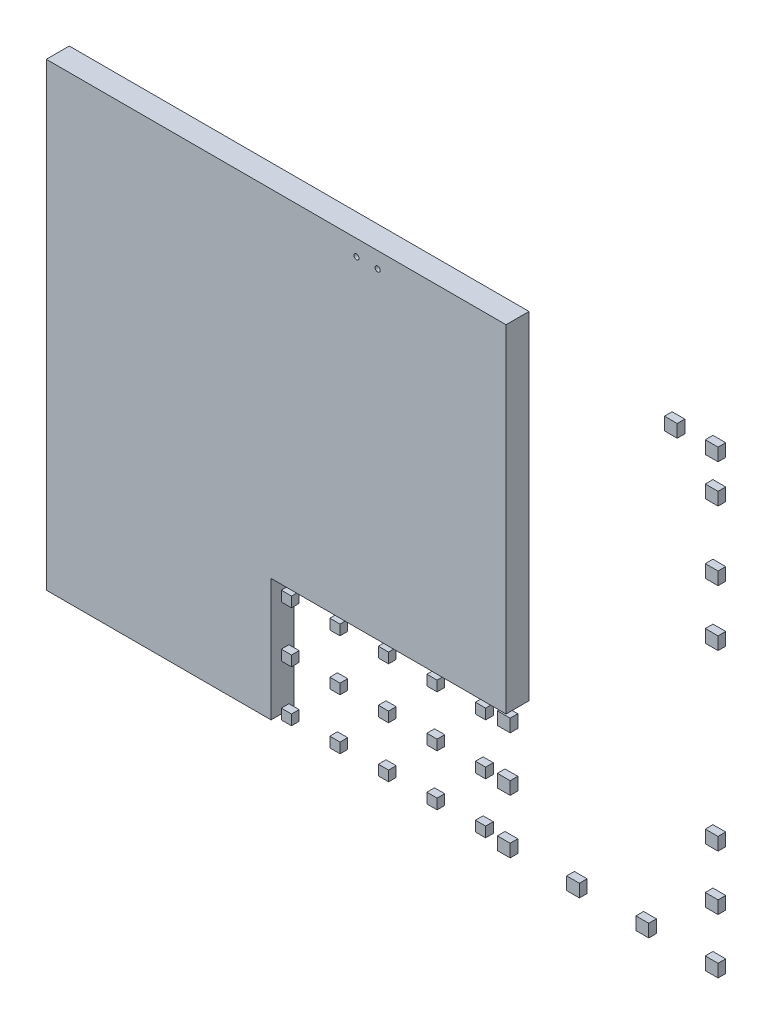
SolidWorks part; units mm, degrees
ref_plane "Спереди" through (0, 0, 0) normal (0, 0, 1) x (1, 0, 0)
ref_plane "Сверху" through (0, 0, 0) normal (0, 1, 0) x (1, 0, 0)
ref_plane "Справа" through (0, 0, 0) normal (1, 0, 0) x (0, 0, -1)
sketch "Эскиз1" plane through (0, 0, 0) normal (0, 0, 1) x (1, 0, 0)
  line L0 (0, 0) -> (9000, 0)
  line L1 (9000, 0) -> (9000, -6600)
  line L2 (9000, -6600) -> (4400, -6600)
  line L3 (4400, -6600) -> (4400, -9000)
  line L4 (4400, -9000) -> (0, -9000)
  line L5 (0, -9000) -> (0, 0)
  line L6 (8830, -6600) -> (8830, -9000) construction
  line L7 (8830, -9000) -> (9080, -9000)
  line L8 (8830, -9000) -> (8830, -8750)
  line L9 (8830, -8750) -> (9080, -8750)
  line L14 (9080, -9000) -> (9080, -8750)
  line L15 (9000, -203) -> (9000, -2700) construction
  line L16 (8797, -6600) -> (4400, -6600) construction
  line L17 (4400, -8797) -> (4400, -6603) construction
  line L18 (203, -9000) -> (4200, -9000) construction
  line L19 (8830, -6630) -> (9080, -6630)
  line L20 (8830, -6630) -> (8830, -6880)
  line L21 (8830, -6880) -> (9080, -6880)
  line L22 (9080, -6630) -> (9080, -6880)
  line L23 (9080, -6880) -> (9080, -7690) construction
  line L24 (8830, -7690) -> (9080, -7690)
  line L25 (8830, -7690) -> (8830, -7940)
  line L26 (8830, -7940) -> (9080, -7940)
  line L27 (9080, -7690) -> (9080, -7940)
  line L28 (9080, -7940) -> (9080, -8750) construction
  line L29 (13150, -9000) -> (0, -9000) construction
  line L30 (10186.6667, -8750) -> (10436.6667, -8750)
  line L31 (10186.6667, -8750) -> (10186.6667, -9000)
  line L32 (10186.6667, -9000) -> (10436.6667, -9000)
  line L33 (10436.6667, -8750) -> (10436.6667, -9000)
  line L34 (9080, -8750) -> (10186.6667, -8750) construction
  line L35 (11543.3333, -8750) -> (11793.3333, -8750)
  line L36 (11543.3333, -8750) -> (11543.3333, -9000)
  line L37 (11543.3333, -9000) -> (11793.3333, -9000)
  line L38 (11793.3333, -8750) -> (11793.3333, -9000)
  line L43 (12900, -8750) -> (13150, -8750)
  line L44 (12900, -8750) -> (12900, -9000)
  line L45 (12900, -9000) -> (13150, -9000)
  line L46 (13150, -8750) -> (13150, -9000)
  line L47 (10436.6667, -8750) -> (11543.3333, -8750) construction
  line L48 (11793.3333, -8750) -> (12900, -8750) construction
  line L49 (13150, -4500) -> (13150, -9000) construction
  line L50 (13150, -6600) -> (12900, -6600)
  line L51 (13150, -6600) -> (13150, -6850)
  line L52 (13150, -6850) -> (12900, -6850)
  line L53 (12900, -6600) -> (12900, -6850)
  line L54 (13150, -7675) -> (12900, -7675)
  line L55 (13150, -7675) -> (13150, -7925)
  line L56 (13150, -7925) -> (12900, -7925)
  line L57 (12900, -7675) -> (12900, -7925)
  line L58 (12900, -7675) -> (12900, -6850) construction
  line L59 (13150, -3450) -> (12900, -3450)
  line L60 (13150, -3450) -> (13150, -3200)
  line L61 (13150, -3200) -> (12900, -3200)
  line L62 (12900, -3450) -> (12900, -3200)
  line L63 (13150, -2100) -> (12900, -2100)
  line L64 (13150, -2100) -> (13150, -2350)
  line L65 (13150, -2350) -> (12900, -2350)
  line L66 (12900, -2100) -> (12900, -2350)
  line L67 (13150, -1000) -> (12900, -1000)
  line L68 (13150, -1000) -> (13150, -750)
  line L69 (13150, -750) -> (12900, -750)
  line L70 (12900, -1000) -> (12900, -750)
  line L71 (13150, 0) -> (12900, 0)
  line L72 (13150, 0) -> (13150, -250)
  line L73 (13150, -250) -> (12900, -250)
  line L74 (12900, 0) -> (12900, -250)
  line L75 (12100, 0) -> (12350, 0)
  line L76 (12100, 0) -> (12100, -250)
  line L77 (12100, -250) -> (12350, -250)
  line L78 (12350, 0) -> (12350, -250)
  line L79 (12900, -7925) -> (12900, -8750) construction
  line L80 (4800, -6900) -> (4800, -7700) construction
  line L81 (4600, -6700) -> (4800, -6700)
  line L82 (4600, -6700) -> (4600, -6900)
  line L83 (4600, -6900) -> (4800, -6900)
  line L84 (4800, -6700) -> (4800, -6900)
  line L85 (4600, -7700) -> (4800, -7700)
  line L86 (4600, -7700) -> (4600, -7900)
  line L87 (4600, -7900) -> (4800, -7900)
  line L88 (4800, -7700) -> (4800, -7900)
  line L89 (4600, -8700) -> (4800, -8700)
  line L90 (4600, -8700) -> (4600, -8900)
  line L91 (4600, -8900) -> (4800, -8900)
  line L92 (4800, -8700) -> (4800, -8900)
  line L93 (4800, -7900) -> (4800, -8700) construction
  line L94 (5550, -6700) -> (5550, -6900)
  line L95 (5550, -6700) -> (5750, -6700)
  line L96 (5750, -6700) -> (5750, -6900)
  line L97 (5550, -6900) -> (5750, -6900)
  line L98 (5550, -7700) -> (5550, -7900)
  line L99 (5550, -7700) -> (5750, -7700)
  line L100 (5750, -7700) -> (5750, -7900)
  line L101 (5550, -7900) -> (5750, -7900)
  line L102 (5550, -8700) -> (5550, -8900)
  line L103 (5550, -8700) -> (5750, -8700)
  line L104 (5750, -8700) -> (5750, -8900)
  line L105 (5550, -8900) -> (5750, -8900)
  line L106 (6500, -6700) -> (6500, -6900)
  line L107 (6500, -6700) -> (6700, -6700)
  line L108 (6700, -6700) -> (6700, -6900)
  line L109 (6500, -6900) -> (6700, -6900)
  line L110 (6500, -7700) -> (6500, -7900)
  line L111 (6500, -7700) -> (6700, -7700)
  line L112 (6700, -7700) -> (6700, -7900)
  line L113 (6500, -7900) -> (6700, -7900)
  line L114 (6500, -8700) -> (6500, -8900)
  line L115 (6500, -8700) -> (6700, -8700)
  line L116 (6700, -8700) -> (6700, -8900)
  line L117 (6500, -8900) -> (6700, -8900)
  line L118 (7450, -6700) -> (7450, -6900)
  line L119 (7450, -6700) -> (7650, -6700)
  line L120 (7650, -6700) -> (7650, -6900)
  line L121 (7450, -6900) -> (7650, -6900)
  line L122 (7450, -7700) -> (7450, -7900)
  line L123 (7450, -7700) -> (7650, -7700)
  line L124 (7650, -7700) -> (7650, -7900)
  line L125 (7450, -7900) -> (7650, -7900)
  line L126 (7450, -8700) -> (7450, -8900)
  line L127 (7450, -8700) -> (7650, -8700)
  line L128 (7650, -8700) -> (7650, -8900)
  line L129 (7450, -8900) -> (7650, -8900)
  line L130 (8400, -6700) -> (8400, -6900)
  line L131 (8400, -6700) -> (8600, -6700)
  line L132 (8600, -6700) -> (8600, -6900)
  line L133 (8400, -6900) -> (8600, -6900)
  line L134 (8400, -7700) -> (8400, -7900)
  line L135 (8400, -7700) -> (8600, -7700)
  line L136 (8600, -7700) -> (8600, -7900)
  line L137 (8400, -7900) -> (8600, -7900)
  line L138 (8400, -8700) -> (8400, -8900)
  line L139 (8400, -8700) -> (8600, -8700)
  line L140 (8600, -8700) -> (8600, -8900)
  line L141 (8400, -8900) -> (8600, -8900)
  circle A0 centre (6486.2448, -312.4922) radius 50
  circle A1 centre (6070.9439, -312.4922) radius 50
  dimension "D3" = 100
  dimension "D1" = 250
  dimension "D2" = 30
  dimension "D4" = 810
  dimension "D5" = 1106.6667
  dimension "D6" = 200
  dimension "D7" = 100
  dimension "D8" = 100
  dimension "D9" = 200
  dimension "D11" = 950
  dimension "D10" = 5
extrude "Бобышка-Вытянуть1" add sketch "Эскиз1" against normal blind 150
sketch "Эскиз2" plane through (0, 0, -150) normal (0, 0, -1) x (-1, 0, 0)
  line L0 (-450, -8550) -> (-450, -450)
  line L1 (-450, -450) -> (-8550, -450)
  line L2 (-8550, -450) -> (-8550, -6150)
  line L3 (-8550, -6150) -> (-3950, -6150)
  line L4 (-3950, -6150) -> (-3950, -8550)
  line L5 (-3950, -8550) -> (-450, -8550)
  line L6 (0, -9000) -> (0, 0)
  line L7 (0, 0) -> (-9000, 0)
  line L8 (-9000, 0) -> (-9000, -6600)
  line L9 (-9000, -6600) -> (-4400, -6600)
  line L10 (-4400, -6600) -> (-4400, -9000)
  line L11 (-4400, -9000) -> (0, -9000)
  line L12 (0, -9000) -> (0, 0)
  line L13 (0, 0) -> (-9000, 0)
  line L14 (-9000, 0) -> (-9000, -6600)
  line L15 (-9000, -6600) -> (-4400, -6600)
  line L16 (-4400, -6600) -> (-4400, -9000)
  line L17 (-4400, -9000) -> (0, -9000)
  dimension "D1" = 0
  dimension "D2" = 450
extrude "Бобышка-Вытянуть2" add sketch "Эскиз2" along normal blind 300
